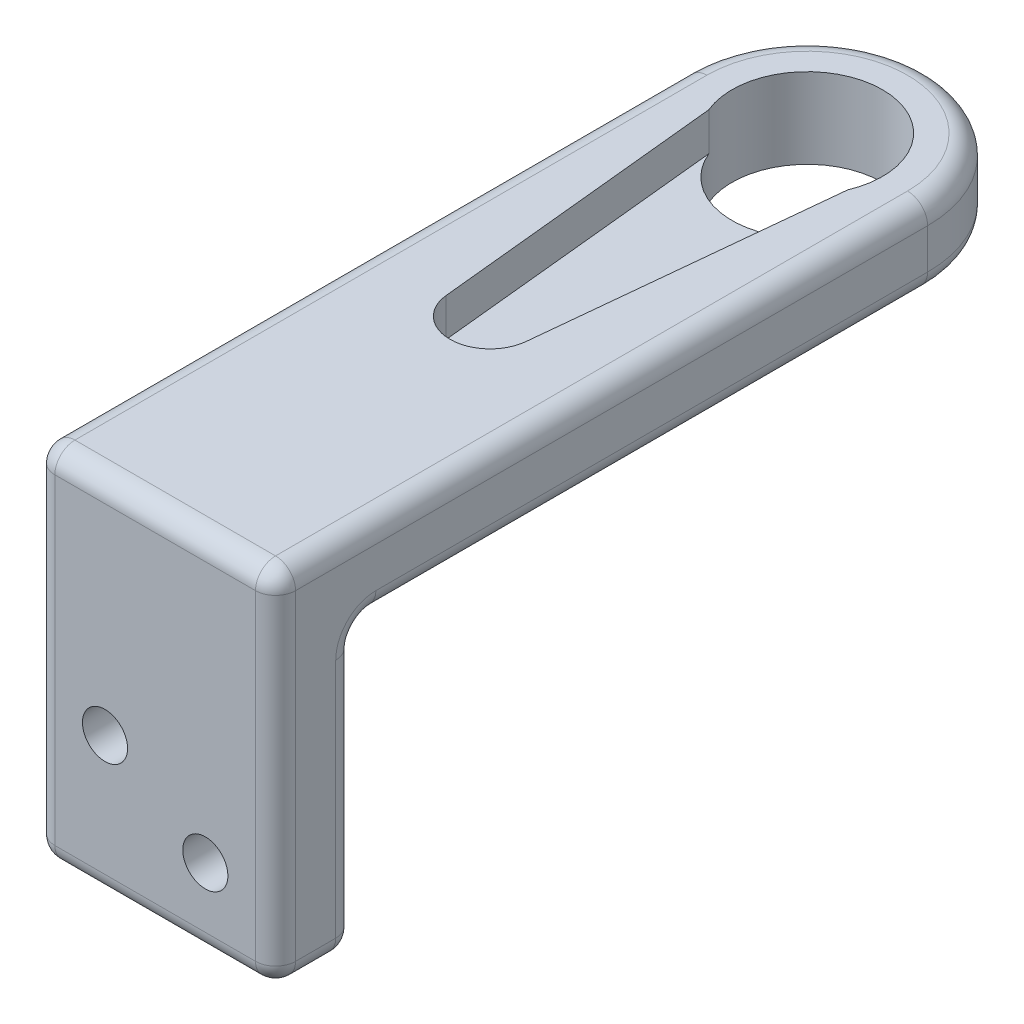
SolidWorks part; units mm, degrees
ref_plane "Front Plane" through (0, 0, 0) normal (0, 0, 1) x (1, 0, 0)
ref_plane "Top Plane" through (0, 0, 0) normal (0, 1, 0) x (1, 0, 0)
ref_plane "Right Plane" through (0, 0, 0) normal (1, 0, 0) x (0, 0, -1)
sketch "Sketch1" plane through (0, 0, 0) normal (0, 1, 0) x (1, 0, 0)
  line L1 (-6, 0) -> (0, 0) construction
  line L4 (-6, 0) -> (-6, -32.5)
  line L5 (-6, -32.5) -> (6, -32.5)
  line L6 (6, -32.5) -> (6, 0)
  arc A1 (-6, 0) -> (6, 0) centre (0, 0) cw
  dimension "D3" = 6
  dimension "D1" = 6
  dimension "D2" = 32.5
extrude "Yaw Arm Base" add sketch "Sketch1" along normal blind 4
sketch "Sketch2" plane through (0, 4, 0) normal (0, 1, 0) x (1, 0, 0)
  circle A0 centre (0, 0) radius 3.75
  dimension "D1" = 7.5
extrude "Yaw Arm Mounting Hole" cut sketch "Sketch2" against normal up to next
sketch "Sketch4" plane through (0, 4, 0) normal (0, 1, 0) x (1, 0, 0)
  line L0 (-3.46, -1.446) -> (-1.9899, -16.006)
  line L1 (3.46, -1.446) -> (1.9899, -16.006)
  line L4 (-6, 0) -> (-6, -32.5) construction
  line L5 (0, -15.8051) -> (0, 0) construction
  arc A0 (-1.9899, -16.006) -> (1.9899, -16.006) centre (0, -15.8051) ccw
  arc A1 (-3.46, -1.446) -> (3.46, -1.446) centre (0, 0) ccw
  circle A2 centre (0, 0) radius 3.75 construction
  dimension "D3" = 2
  dimension "D1" = 14.56
  dimension "D2" = 2.54
extrude "Yaw Arm Slot" cut sketch "Sketch4" against normal blind 1.9
sketch "Sketch5" plane through (0, 0, 0) normal (0, -1, 0) x (1, 0, 0)
  line L1 (-6, 32.5) -> (6, 32.5)
  line L2 (-6, 32.5) -> (-6, 28.5)
  line L3 (-6, 28.5) -> (6, 28.5)
  line L4 (6, 32.5) -> (6, 28.5)
  point P5 (0, 0)
  dimension "D1" = 4
extrude "Mounting Bracket" add sketch "Sketch5" along normal blind 14
sketch "Sketch8" plane through (0, 0, 28.5) normal (0, 0, -1) x (-1, 0, 0)
  line L0 (0, 0) -> (0, -14) construction
  line L1 (6, -14) -> (-6, -14) construction
  line L2 (-6, 0) -> (6, 0) construction
  circle A0 centre (-2.5, -10) radius 1.125
  circle A1 centre (2.5, -7) radius 1.125
  point P11 (-3.701, -10)
  point P12 (0, 0)
  point P13 (2.7698, -7)
  dimension "D1" = 2.25
  dimension "D2" = 2.25
  dimension "D3" = 4
  dimension "D4" = 7
  dimension "D5" = 2.5
  dimension "D6" = 2.5
extrude "Bracket Mounting Holes" cut sketch "Sketch8" against normal up to next
fillet "1mm Fillets" radius 1 16 edges at (6, -7, 28.5) (-6, -7, 28.5) (6, 4, 16.25) (0, 4, -6) (6, 0, 14.25) (0, 0, -6) (0, 4, 32.5) (6, -5, 32.5) (-6, -5, 32.5) (0, -14, 32.5) (6, -14, 30.5) (0, -14, 28.5) (-6, -14, 30.5) (-6, 4, 16.25) (-6, 0, 14.25) (0, 0, 28.5)
